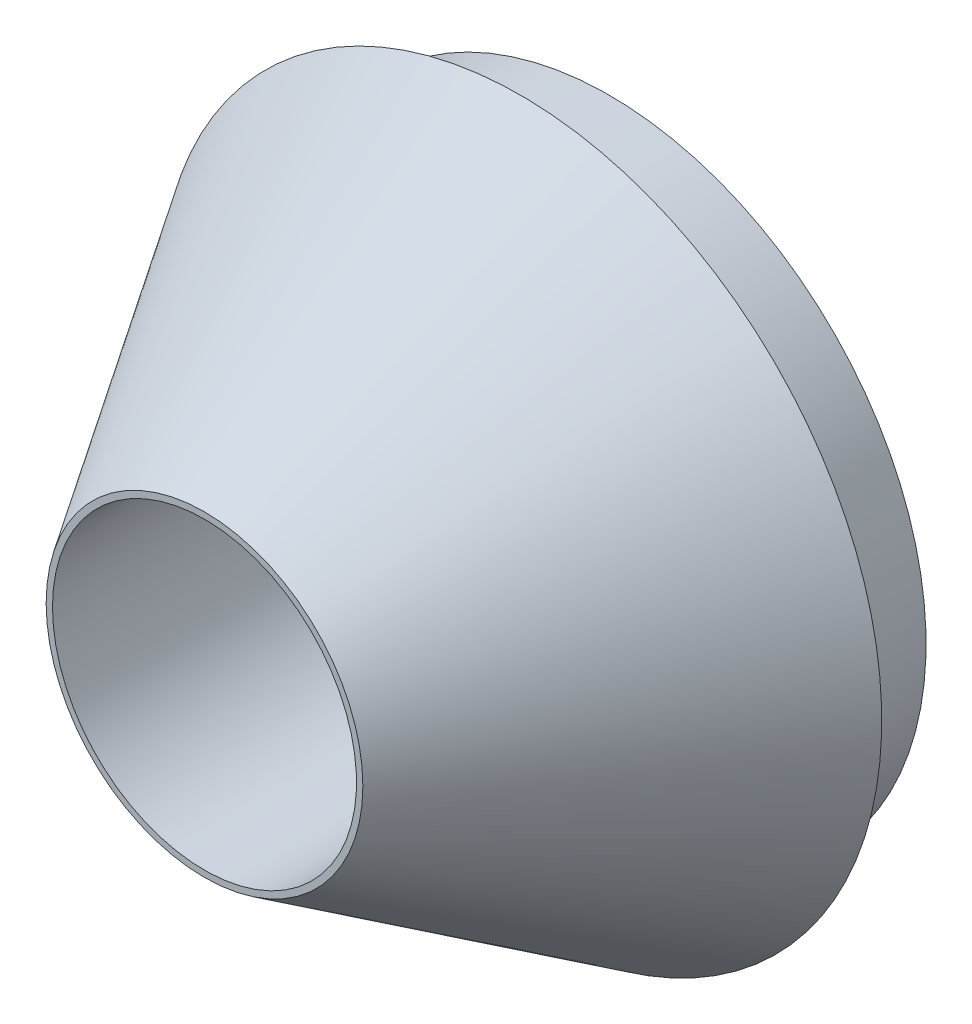
SolidWorks part; units mm, degrees
ref_plane "Front Plane" through (0, 0, 0) normal (0, 0, 1) x (1, 0, 0)
ref_plane "Top Plane" through (0, 0, 0) normal (0, 1, 0) x (1, 0, 0)
ref_plane "Right Plane" through (0, 0, 0) normal (1, 0, 0) x (0, 0, -1)
sketch "Sketch1" plane through (0, 0, 0) normal (0, 1, 0) x (1, 0, 0)
  line L0 (0, 0) -> (6.35, 0)
  line L1 (6.35, 0) -> (14.478, 12.6787)
  line L2 (14.478, 12.6787) -> (12.7, 12.6787)
  line L3 (12.7, 12.6787) -> (12.7, 16.2347)
  line L4 (12.7, 16.2347) -> (0, 16.2347)
  line L5 (0, 16.2347) -> (0, 0)
  point P3 (0, 16.2347)
  dimension "D1" = 6.35
  dimension "D2" = 1.778
  dimension "D3" = 12.7
  dimension "D4" = 3.556
revolve "Revolve2" add sketch "Sketch1" angle 360 about L5
sketch "Sketch2" plane through (0, 0, -16.2347) normal (0, 0, -1) x (-1, 0, 0)
  circle A0 centre (0, 0) radius 6.096
  dimension "D1" = 12.192
extrude "Cut-Extrude1" cut sketch "Sketch2" against normal blind 17.78
